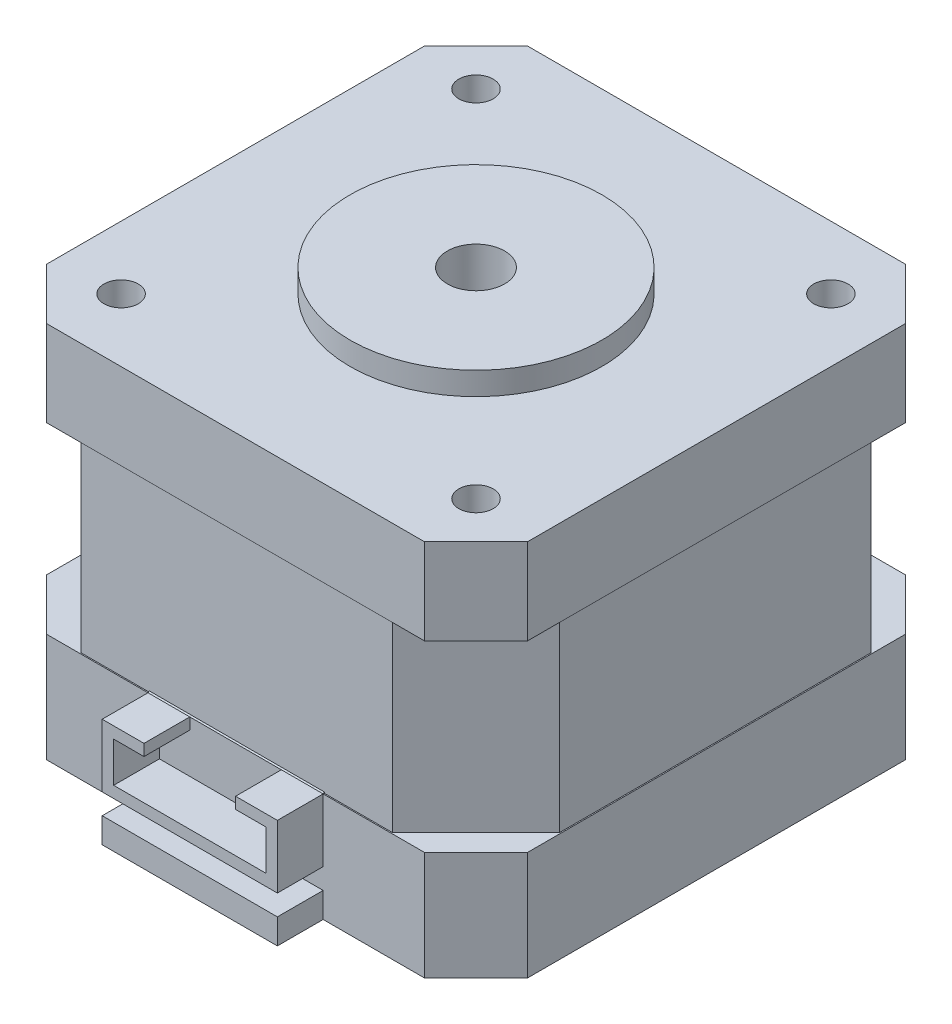
SolidWorks part; units mm, degrees
ref_plane "前视基准面" through (0, 0, 0) normal (0, 0, 1) x (1, 0, 0)
ref_plane "上视基准面" through (0, 0, 0) normal (0, 1, 0) x (1, 0, 0)
ref_plane "右视基准面" through (0, 0, 0) normal (1, 0, 0) x (0, 0, -1)
other "Configuration Table"
sketch "草图1" plane through (0, 0, 0) normal (0, 1, 0) x (1, 0, 0)
  line L1 (-21, -21) -> (21, -21)
  line L2 (-21, -21) -> (-21, 21)
  line L3 (-21, 21) -> (21, 21)
  line L4 (21, -21) -> (21, 21)
  line L5 (-21, -21) -> (21, 21) construction
  line L6 (-21, 21) -> (21, -21) construction
  point P0 (0, 0)
  dimension "D1" = 42
  dimension "D2" = 42
extrude "凸台-拉伸1" add sketch "草图1" along normal blind 33
sketch "草图2" plane through (0, 0, 0) normal (0, 1, 0) x (1, 0, 0)
  line L0 (0, 21) -> (0, -21) construction
  line L1 (21, 21) -> (-21, 21) construction
  line L2 (-21, -21) -> (21, -21) construction
  line L3 (-21, 0) -> (21, 0) construction
  line L4 (-21, 21) -> (-21, -21) construction
  line L5 (21, -21) -> (21, 21) construction
  line L6 (-21, 21) -> (-21, 16.5)
  line L7 (-21, 16.5) -> (-16.5, 21)
  line L8 (-16.5, 21) -> (-21, 21)
  line L9 (-21, -21) -> (-21, -16.5)
  line L10 (-16.5, -21) -> (-21, -21)
  line L11 (-21, -16.5) -> (-16.5, -21)
  line L12 (21, -21) -> (21, -16.5)
  line L13 (16.5, -21) -> (21, -21)
  line L14 (21, -16.5) -> (16.5, -21)
  line L15 (21, 21) -> (21, 16.5)
  line L16 (16.5, 21) -> (21, 21)
  line L17 (21, 16.5) -> (16.5, 21)
  dimension "D1" = 4.5
  dimension "D2" = 4.5
extrude "切除-拉伸1" cut sketch "草图2" against normal up to surface (33 mm away) from surface at 33 up to face at (0, 0, 0) starting at face at (0, 33, 0)
sketch "草图3" plane through (0, 0, 0) normal (0, 1, 0) x (1, 0, 0)
  line L0 (-21, 0) -> (21, 0) construction
  line L1 (-21, 16.5) -> (-21, -16.5) construction
  line L2 (21, -16.5) -> (21, 16.5) construction
  line L3 (0, 21) -> (0, -21) construction
  line L4 (16.5, 21) -> (-16.5, 21) construction
  line L5 (-16.5, -21) -> (16.5, -21) construction
  line L6 (-21, 13.5) -> (-21, 21)
  line L7 (-21, 21) -> (-13.5, 21)
  line L8 (-13.5, 21) -> (-21, 13.5)
  line L9 (-21, -13.5) -> (-21, -21)
  line L10 (-13.5, -21) -> (-21, -13.5)
  line L11 (-21, -21) -> (-13.5, -21)
  line L12 (21, -13.5) -> (21, -21)
  line L13 (21, -21) -> (13.5, -21)
  line L14 (13.5, -21) -> (21, -13.5)
  line L15 (21, 13.5) -> (21, 21)
  line L16 (21, 21) -> (13.5, 21)
  line L17 (13.5, 21) -> (21, 13.5)
  dimension "D1" = 7.5
  dimension "D2" = 7.5
extrude "切除-拉伸2" cut sketch "草图3" along normal blind 16 from offset 9.5
sketch "草图4" plane through (0, 0, 0) normal (0, 0, 1) x (1, 0, 0)
  line L5 (-16.5, 25.5) -> (16.5, 25.5)
  line L6 (-16.5, 25.5) -> (-16.5, 9.5)
  line L7 (-16.5, 9.5) -> (16.5, 9.5)
  line L8 (16.5, 25.5) -> (16.5, 9.5)
extrude "切除-拉伸3" cut sketch "草图4" against normal blind 0.1 from surface at 21 starting at face at (0, 17.1667, 21)
sketch "草图5" plane through (0, 0, 0) normal (0, 0, 1) x (1, 0, 0)
  line L5 (-16.5, 25.5) -> (16.5, 25.5)
  line L6 (-16.5, 25.5) -> (-16.5, 9.5)
  line L7 (-16.5, 9.5) -> (16.5, 9.5)
  line L8 (16.5, 25.5) -> (16.5, 9.5)
extrude "切除-拉伸4" cut sketch "草图5" along normal blind 0.1 from surface at -21 starting at face at (0, 17.1667, -21)
sketch "草图6" plane through (0, 0, 0) normal (1, 0, 0) x (0, 0, -1)
  line L5 (-16.5, 25.5) -> (16.5, 25.5)
  line L6 (-16.5, 25.5) -> (-16.5, 9.5)
  line L7 (-16.5, 9.5) -> (16.5, 9.5)
  line L8 (16.5, 25.5) -> (16.5, 9.5)
extrude "切除-拉伸5" cut sketch "草图6" along normal blind 0.1 from surface at -21 starting at face at (-21, 17.1667, 0)
sketch "草图7" plane through (0, 0, 0) normal (1, 0, 0) x (0, 0, -1)
  line L5 (-16.5, 25.5) -> (16.5, 25.5)
  line L6 (-16.5, 25.5) -> (-16.5, 9.5)
  line L7 (-16.5, 9.5) -> (16.5, 9.5)
  line L8 (16.5, 25.5) -> (16.5, 9.5)
extrude "切除-拉伸6" cut sketch "草图7" against normal blind 0.1 from surface at 21 starting at face at (21, 17.1667, 0)
sketch "草图8" plane through (0, 0, 0) normal (0, 1, 0) x (1, 0, 0)
  circle A0 centre (0, 0) radius 4.75
  dimension "D1" = 9.5
extrude "切除-拉伸7" cut sketch "草图8" along normal blind 3 from surface at 0 starting at face at (0, 0, 0)
sketch "草图9" plane through (0, 0, 0) normal (0, 1, 0) x (1, 0, 0)
  circle A0 centre (0, 0) radius 11
  dimension "D1" = 22
extrude "凸台-拉伸2" add sketch "草图9" along normal blind 2 from surface at 33 starting at face at (0, 33, 0)
sketch "草图11" plane through (0, 0, 0) normal (0, 1, 0) x (1, 0, 0)
  circle A0 centre (0, 0) radius 2.5
  dimension "D1" = 5
extrude "切除-拉伸8" cut sketch "草图11" against normal up to surface (35 mm away) from surface at 35 up to face at (0, 0, -4.75) starting at face at (0, 35, -11)
sketch "草图12" plane through (0, 0, 0) normal (0, 1, 0) x (1, 0, 0)
  line L1 (-15.5, -15.5) -> (15.5, -15.5) construction
  line L2 (-15.5, -15.5) -> (-15.5, 15.5) construction
  line L3 (-15.5, 15.5) -> (15.5, 15.5) construction
  line L4 (15.5, -15.5) -> (15.5, 15.5) construction
  line L5 (-15.5, -15.5) -> (15.5, 15.5) construction
  line L6 (-15.5, 15.5) -> (15.5, -15.5) construction
  circle A0 centre (-15.5, 15.5) radius 1.5
  circle A1 centre (-15.5, -15.5) radius 1.5
  circle A2 centre (15.5, -15.5) radius 1.5
  circle A3 centre (15.5, 15.5) radius 1.5
  point P0 (0, 0)
  dimension "D3" = 3
  dimension "D4" = 3
  dimension "D5" = 3
  dimension "D6" = 3
  dimension "D1" = 31
  dimension "D2" = 31
extrude "切除-拉伸9" cut sketch "草图12" against normal up to surface (33 mm away) from surface at 33 up to face at (0, 0, -4.75) starting at face at (0, 33, -11)
sketch "草图13" plane through (0, 0, 0) normal (0, 0, 1) x (1, 0, 0)
  line L0 (-16.5, 0) -> (16.5, 0) construction
  line L1 (-7.65, 2.2) -> (7.65, 2.2)
  line L2 (-7.65, 2.2) -> (-7.65, 0)
  line L3 (-7.65, 0) -> (7.65, 0)
  line L4 (7.65, 2.2) -> (7.65, 0)
  point P6 (0, 2.2)
  dimension "D1" = 15.3
  dimension "D2" = 2.2
extrude "凸台-拉伸3" add sketch "草图13" along normal blind 4 from surface at 21 starting at face at (0, 4.75, 21)
sketch "草图17" plane through (0, 0, 0) normal (0, 0, 1) x (1, 0, 0)
  line L0 (-13.6, 9.5) -> (13.6, 9.5) construction
  line L1 (-7.65, 9.5) -> (7.65, 9.5)
  line L2 (-7.65, 9.5) -> (-7.65, 4)
  line L3 (-7.65, 4) -> (7.65, 4)
  line L4 (7.65, 9.5) -> (7.65, 4)
  line L5 (-7.65, 2.2) -> (-7.65, 0) construction
  line L6 (7.65, 0) -> (7.65, 2.2) construction
  dimension "D1" = 5.5
extrude "凸台-拉伸7" add sketch "草图17" along normal up to surface (4 mm away) from surface at 21 up to face at (0, 1.1, 25) starting at face at (0, 2.925, 21)
sketch "草图18" plane through (0, 0, 0) normal (0, 0, 1) x (1, 0, 0)
  line L0 (-7.65, 4) -> (7.65, 4) construction
  line L1 (-6.65, 8.5) -> (-4, 8.5)
  line L2 (-6.65, 8.5) -> (-6.65, 5)
  line L3 (-6.65, 5) -> (6.65, 5)
  line L4 (6.65, 8.5) -> (6.65, 5)
  line L5 (-7.65, 9.5) -> (-7.65, 4) construction
  line L6 (-4, 8.5) -> (-4, 9.5)
  line L7 (-13.6, 9.5) -> (13.6, 9.5) construction
  line L8 (-4, 9.5) -> (4, 9.5)
  line L9 (4, 9.5) -> (4, 8.5)
  line L10 (4, 8.5) -> (6.65, 8.5)
  point P13 (0, 9.5)
  dimension "D1" = 13.3
  dimension "D2" = 3.5
  dimension "D3" = 1
  dimension "D4" = 1
  dimension "D5" = 8
extrude "切除-拉伸11" cut sketch "草图18" against normal up to surface (4 mm away) from surface at 25 up to face at (0, 4.2, 21) starting at face at (0, 6.75, 25)
sketch "草图19" plane through (0, 0, 0) normal (1, 0, 0) x (0, 0, -1)
  line L0 (-21, 9.5) -> (-20.9, 9.5)
  line L1 (-13.6, 9.5) -> (-20.9, 9.5) construction
  line L2 (-16.5, 9.5) -> (-21, 9.5) construction
  line L3 (-20.9, 9.5) -> (-20.9, 9.6)
  line L4 (-20.9, 25.5) -> (-20.9, 9.5) construction
  line L5 (-20.9, 9.6) -> (-21, 9.5)
  dimension "D1" = 0.1
  dimension "D2" = 0.1
extrude "凸台-拉伸8" add sketch "草图19" against normal up to surface (15.3 mm away) from surface at 7.65 up to face at (-7.65, 6.75, 23) starting at face at (7.65, 6.75, 23)
